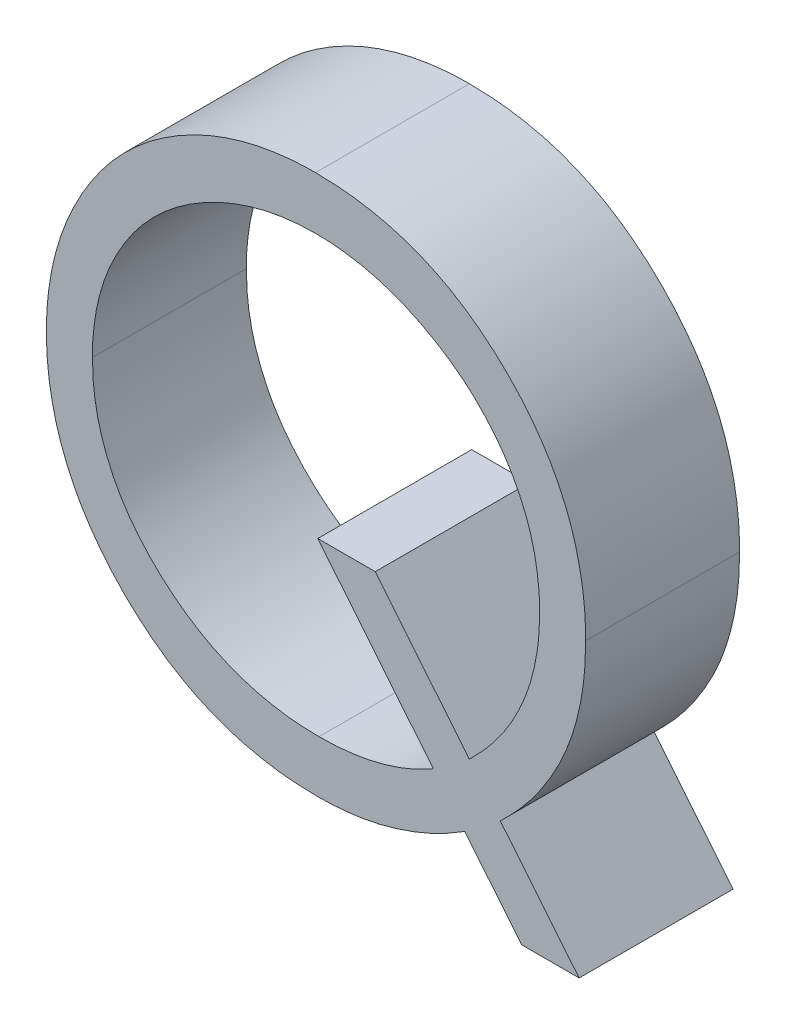
SolidWorks part; units mm, degrees
ref_plane "Plan de face" through (0, 0, 0) normal (0, 0, 1) x (1, 0, 0)
ref_plane "Plan de dessus" through (0, 0, 0) normal (0, 1, 0) x (1, 0, 0)
ref_plane "Plan de droite" through (0, 0, 0) normal (1, 0, 0) x (0, 0, -1)
sketch "Esquisse1" plane through (0, 0, 0) normal (0, 0, 1) x (1, 0, 0)
  text T0 "Q" font "Century Gothic" height 5
extrude "Boss.-Extru.1" add sketch "Esquisse1" along normal blind 1.5
